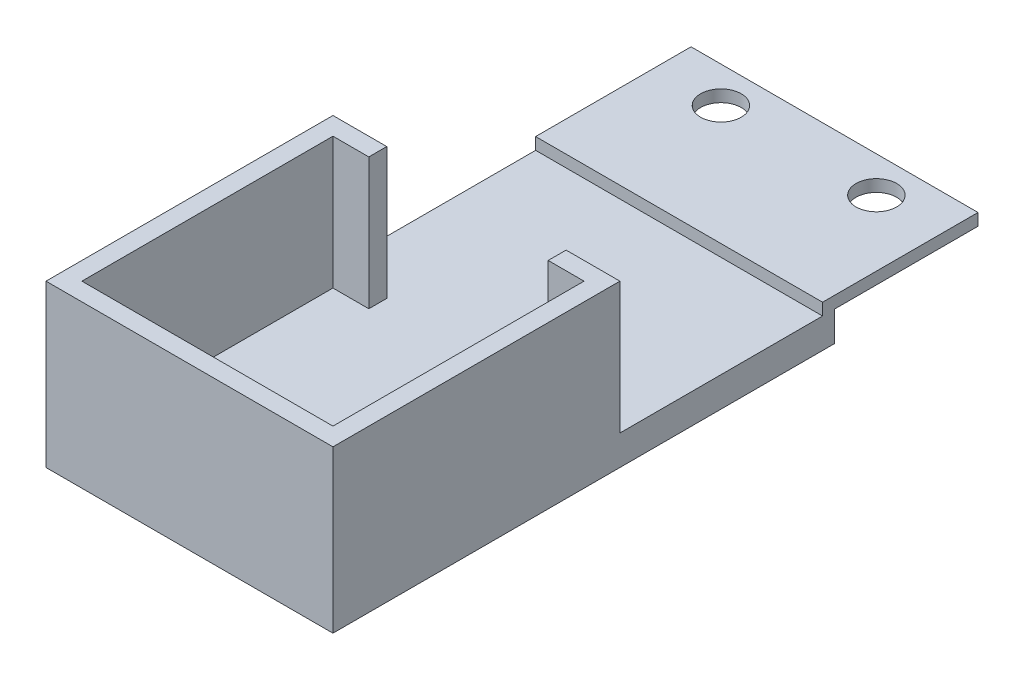
SolidWorks part; units mm, degrees
ref_plane "Front Plane" through (0, 0, 0) normal (0, 0, 1) x (1, 0, 0)
ref_plane "Top Plane" through (0, 0, 0) normal (0, 1, 0) x (1, 0, 0)
ref_plane "Right Plane" through (0, 0, 0) normal (1, 0, 0) x (0, 0, -1)
sketch "Sketch3" plane through (0, 0, 0) normal (1, 0, 0) x (0, 0, -1)
  line L0 (0, 0) -> (0, 5)
  line L1 (0, 5) -> (24, 5)
  line L2 (0, 0) -> (-83.9, 0)
  line L3 (-2, 2) -> (-83.9, 2)
  line L4 (-2, 2) -> (-2, 7)
  line L5 (-2, 7) -> (24, 7)
  line L6 (24, 7) -> (24, 5)
  line L7 (-83.9, 2) -> (-83.9, 0)
  dimension "D1" = 5
  dimension "D2" = 24
  dimension "D3" = 83.9
  dimension "D4" = 2
extrude "Boss-Extrude1" add sketch "Sketch3" along normal blind 48
sketch "Sketch4" plane through (0, 2, 0) normal (0, 1, 0) x (1, 0, 0)
  line L0 (48, -2) -> (48, -83.9) construction
  line L1 (0, -83.9) -> (48, -83.9)
  line L2 (0, -83.9) -> (0, -35.9)
  line L3 (0, -35.9) -> (48, -35.9)
  line L4 (48, -83.9) -> (48, -35.9)
  line L5 (3, -38.9) -> (45, -38.9)
  line L6 (45, -80.9) -> (45, -38.9)
  line L7 (3, -80.9) -> (45, -80.9)
  line L8 (3, -80.9) -> (3, -38.9)
  dimension "D1" = 48
  dimension "D2" = 3
extrude "Boss-Extrude2" add sketch "Sketch4" along normal blind 25
sketch "Sketch5" plane through (0, 2, 0) normal (0, 1, 0) x (1, 0, 0)
  line L4 (45, -38.9) -> (3, -38.9)
  line L5 (3, -38.9) -> (3, -80.9)
  line L6 (3, -80.9) -> (45, -80.9)
  line L7 (45, -80.9) -> (45, -38.9)
  line L8 (45, -38.9) -> (3, -38.9)
  line L9 (3, -38.9) -> (3, -80.9)
  line L10 (3, -80.9) -> (45, -80.9)
  line L11 (45, -80.9) -> (45, -38.9)
  dimension "D1" = 0
extrude "Boss-Extrude3" add sketch "Sketch5" along normal blind 3
sketch "Sketch7" plane through (0, 7, 0) normal (0, 1, 0) x (1, 0, 0)
  line L0 (48, 24) -> (0, 24) construction
  line L1 (0, 24) -> (0, -2) construction
  line L2 (24, 24) -> (24, -2) construction
  line L3 (48, -2) -> (0, -2) construction
  circle A0 centre (11, 18) radius 3.4
  circle A1 centre (37, 18) radius 3.4
  dimension "D1" = 6.8
  dimension "D3" = 11
  dimension "D2" = 6
extrude "Cut-Extrude1" cut sketch "Sketch7" against normal through all
sketch "Sketch8" plane through (0, 0, 35.9) normal (0, 0, -1) x (-1, 0, 0)
  line L0 (-24, 27) -> (-24, 2) construction
  line L8 (-48, 27) -> (0, 27) construction
  line L9 (-48, 2) -> (0, 2) construction
  line L19 (-39, 27) -> (-9, 27)
  line L20 (-39, 27) -> (-39, 2)
  line L21 (-39, 2) -> (-9, 2)
  line L22 (-9, 27) -> (-9, 2)
  line L23 (-39, 27) -> (-9, 2) construction
  line L24 (-39, 2) -> (-9, 27) construction
  point P4 (-24, 14.5)
  dimension "D1" = 30
extrude "Cut-Extrude3" cut sketch "Sketch8" against normal blind 10
sketch "Sketch9" plane through (0, 2, 0) normal (0, 1, 0) x (1, 0, 0)
  line L0 (0, -2) -> (0, -35.9)
  line L1 (0, -35.9) -> (9, -35.9)
  line L2 (9, -35.9) -> (9, -45.9)
  line L3 (9, -45.9) -> (39, -45.9)
  line L4 (39, -45.9) -> (39, -35.9)
  line L5 (39, -35.9) -> (48, -35.9)
  line L6 (48, -35.9) -> (48, -2)
  line L7 (48, -2) -> (0, -2)
extrude "Boss-Extrude4" add sketch "Sketch9" along normal up to surface (3 mm away) up to face at (24, 5, 51.15)
